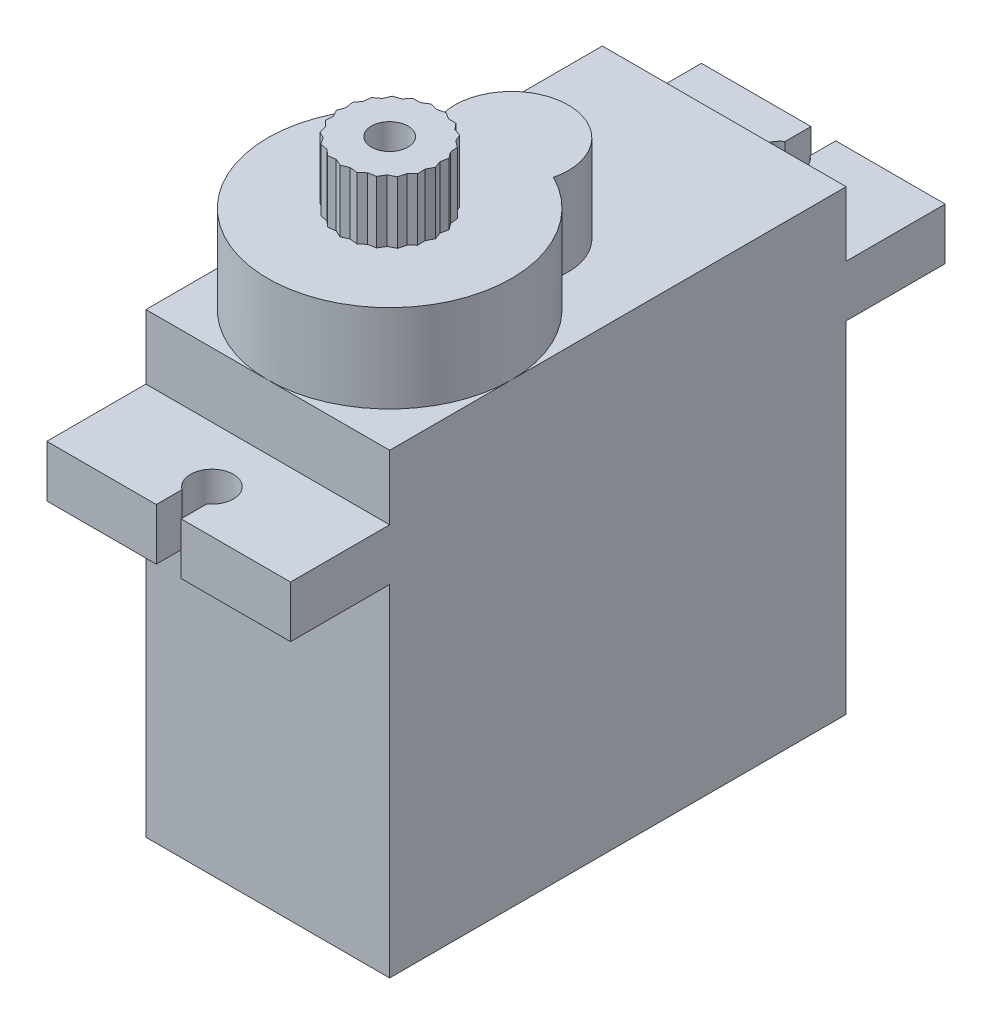
SolidWorks part; units mm, degrees
ref_plane "Front Plane" through (0, 0, 0) normal (0, 0, 1) x (1, 0, 0)
ref_plane "Top Plane" through (0, 0, 0) normal (0, 1, 0) x (1, 0, 0)
ref_plane "Right Plane" through (0, 0, 0) normal (1, 0, 0) x (0, 0, -1)
sketch "Sketch1" plane through (0, 0, 0) normal (1, 0, 0) x (0, 0, -1)
  line L0 (22.45, 16.764) -> (27.325, 16.764)
  line L1 (0, 0) -> (22.45, 0)
  line L2 (0, 0) -> (0, 16.764)
  line L3 (0, 22.479) -> (22.45, 22.479)
  line L4 (22.45, 0) -> (22.45, 16.764)
  line L5 (-4.875, 16.764) -> (0, 16.764)
  line L6 (-4.875, 16.764) -> (-4.875, 19.304)
  line L7 (-4.875, 19.304) -> (0, 19.304)
  line L8 (27.325, 16.764) -> (27.325, 19.304)
  line L9 (22.45, 19.304) -> (22.45, 22.479)
  line L10 (22.45, 19.304) -> (27.325, 19.304)
  line L11 (0, 19.304) -> (0, 22.479)
  dimension "D1" = 16.764
  dimension "D2" = 32.2
  dimension "D3" = 22.45
  dimension "D4" = 22.479
  dimension "D5" = 2.54
extrude "Boss-Extrude1" add sketch "Sketch1" along normal mid plane 11.9888
sketch "Sketch2" plane through (0, 22.479, 0) normal (0, 1, 0) x (1, 0, 0)
  line L0 (5.9944, 0) -> (-5.9944, 0) construction
  line L1 (-5.9944, 22.45) -> (-5.9944, 0) construction
  arc A0 (-2.7171, 11.3377) -> (2.7171, 11.3377) centre (0, 5.9944) ccw
  arc A1 (2.7171, 11.3377) -> (-2.7171, 11.3377) centre (0, 11.9888) ccw
  point P1 (2.1623, 10.6389)
  dimension "D1" = 2.794
extrude "Boss-Extrude2" add sketch "Sketch2" along normal blind 4.318
sketch "Sketch3" plane through (0, 26.797, 0) normal (0, 1, 0) x (1, 0, 0)
  line L0 (0, 5.9944) -> (0, 8.3058)
  line L1 (0, 8.3058) -> (0.3634, 8.4056)
  line L2 (0.3634, 8.4056) -> (0.6813, 8.2031)
  line L3 (0.6813, 8.2031) -> (0, 5.9944)
  circle A0 centre (0, 5.9944) radius 2.3114 construction
  circle A1 centre (0, 5.9944) radius 2.4384 construction
  point P8 (1.5791, 10.4897)
  dimension "D1" = 4.8768
  dimension "D2" = 4.6228
  dimension "D3" = 17.143
extrude "Boss-Extrude3" add sketch "Sketch3" along normal blind 3.048
pattern_circular "CirPattern1" count 21 over 360 about axis through (0, 0, -5.9944) along (0, 1, 0) of "Boss-Extrude3"
sketch "Sketch4" plane through (0, 29.845, 0) normal (0, 1, 0) x (1, 0, 0)
  circle A0 centre (0, 5.9944) radius 0.9
  dimension "D1" = 1.8
extrude "Cut-Extrude1" cut sketch "Sketch4" against normal blind 6
sketch "Sketch5" plane through (0, 19.304, 0) normal (0, 1, 0) x (1, 0, 0)
  line L0 (-0.6096, 26.055) -> (-0.6096, 27.325)
  line L1 (5.9944, 27.325) -> (-5.9944, 27.325) construction
  line L2 (-0.6096, 27.325) -> (0.6096, 27.325)
  line L3 (0.6096, 27.325) -> (0.6096, 26.055)
  line L4 (-0.6096, -4.875) -> (0.6096, -4.875)
  line L5 (5.9944, -4.875) -> (-5.9944, -4.875) construction
  line L6 (0.6096, -4.875) -> (0.6096, -3.605)
  line L7 (-0.6096, -4.875) -> (-0.6096, -3.605)
  arc A0 (-0.6096, 26.055) -> (0.6096, 26.055) centre (0, 25.195) ccw
  arc A1 (0.6096, -3.605) -> (-0.6096, -3.605) centre (0, -2.745) ccw
  point P6 (0, 0)
  point P7 (0, 0)
  point P15 (0, -3.0705)
  dimension "D2" = 1.0541
  dimension "D1" = 1.2192
  dimension "D3" = 27.94
extrude "Cut-Extrude2" cut sketch "Sketch5" against normal up to next
